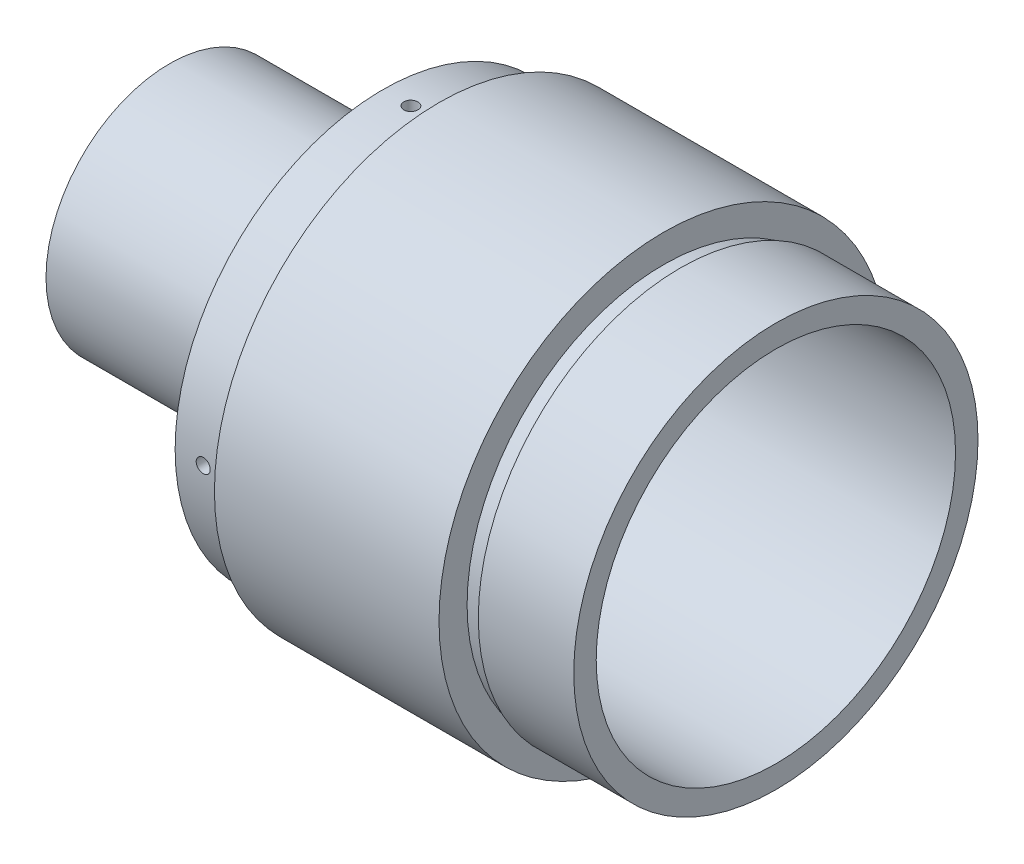
SolidWorks part; units mm, degrees
ref_plane "Ön Düzlem" through (0, 0, 0) normal (0, 0, 1) x (1, 0, 0)
ref_plane "Üst Düzlem" through (0, 0, 0) normal (0, 1, 0) x (1, 0, 0)
ref_plane "Sağ Düzlem" through (0, 0, 0) normal (1, 0, 0) x (0, 0, -1)
ref_axis "Eksen1" through (-88.99, 0, 0) along (1, 0, 0)
sketch "Çizim1" plane through (0, 0, 0) normal (0, 0, 1) x (1, 0, 0)
  line L2 (-60, 40) -> (-60, 37)
  line L3 (-60, 37) -> (-70, 37)
  line L4 (-70, 37) -> (-70, 22)
  line L10 (-57, 18.2) -> (-57, 32)
  line L11 (-57, 32) -> (0, 32)
  line L12 (0, 32) -> (0, 36)
  line L14 (-20, 40) -> (-60, 40)
  line L20 (-20, 40) -> (-20, 35)
  line L21 (-20, 35) -> (-17, 35)
  line L22 (-17, 35) -> (-17, 36)
  line L23 (-17, 36) -> (0, 36)
  line L24 (-57, 18.2) -> (-106, 18.2)
  line L25 (-106, 18.2) -> (-106, 4)
  line L26 (-106, 4) -> (-108, 4)
  line L27 (-108, 4) -> (-108, 22)
  line L28 (-70, 22) -> (-108, 22)
  dimension "D1" = 4
revolve "Döndür1" add sketch "Çizim1" angle 360 about axis through (-88.99, 0, 0) along (1, 0, 0)
sketch "Çizim12" plane through (0, 0, 0) normal (1, 0, 0) x (0, 0, -1)
  circle A0 centre (12.5, 0) radius 1.6
extrude "Kes-Ekstrüzyon1" cut sketch "Çizim12" against normal through all
pattern_circular "Dairesel Kaplama1" count 6 over 360 about axis through (0, 0, 0) along (1, 0, 0) of "Kes-Ekstrüzyon1"
sketch "Çizim13" plane through (0, 0, 0) normal (0, 0, 1) x (1, 0, 0)
  line L2 (-88.99, 0) -> (88.99, 0) construction
  circle A0 centre (-65, 0) radius 1.25
extrude "Kes-Ekstrüzyon2" cut sketch "Çizim13" along normal blind 10 from offset 27
pattern_circular "Dairesel Kaplama2" count 4 over 360 about axis through (0, 0, 0) along (1, 0, 0) of "Kes-Ekstrüzyon2"
